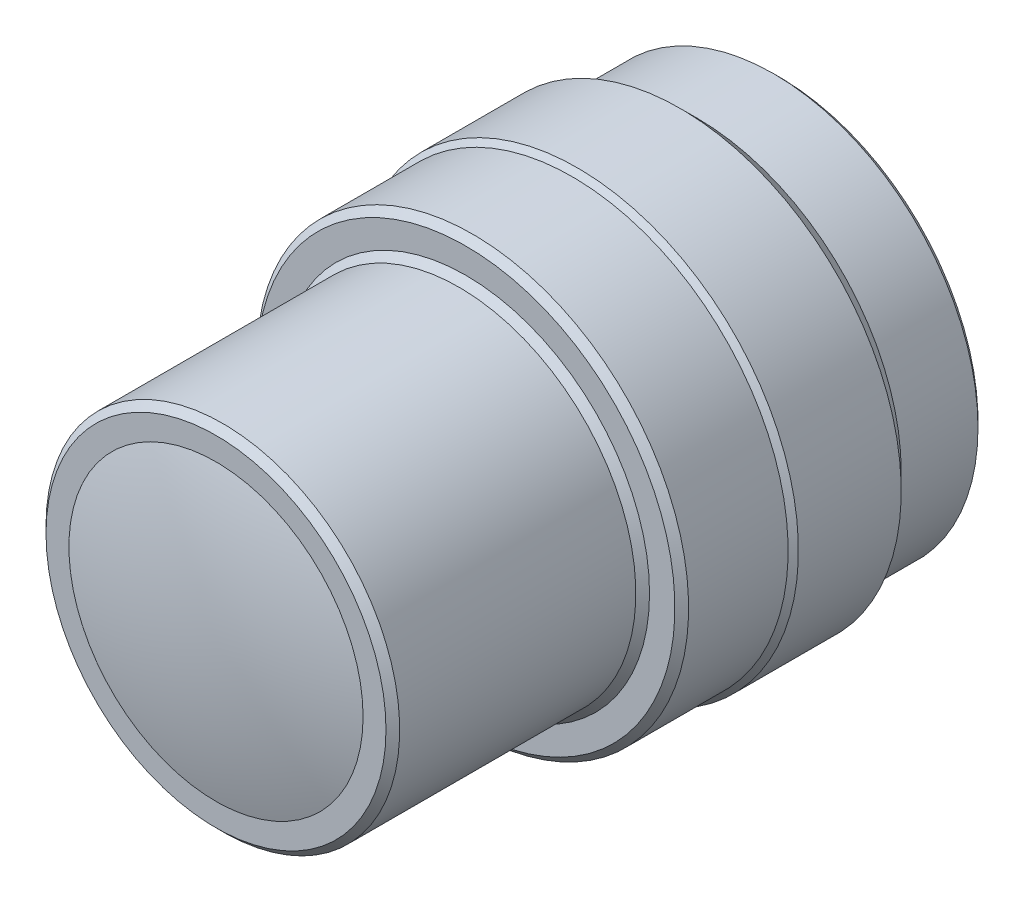
SolidWorks part; units mm, degrees
material "объектив"
ref_plane "Спереди" through (0, 0, 0) normal (0, 0, 1) x (1, 0, 0)
ref_plane "Сверху" through (0, 0, 0) normal (0, 1, 0) x (1, 0, 0)
ref_plane "Справа" through (0, 0, 0) normal (1, 0, 0) x (0, 0, -1)
sketch "Эскиз1" plane through (0, 0, 0) normal (0, 1, 0) x (1, 0, 0)
  line L0 (0, 0) -> (12.7, 0)
  line L1 (12.7, 0) -> (12.7, -3)
  line L2 (12.7, -3) -> (15, -3)
  line L3 (15, -3) -> (15, -4)
  line L4 (15, -4) -> (29, -4)
  line L5 (29, -4) -> (29.8, -4.8)
  line L6 (29.8, -4.8) -> (29.8, -16)
  line L7 (29.8, -16) -> (32.25, -18.45)
  line L8 (32.25, -18.45) -> (32.25, -33.45)
  line L9 (32.25, -33.45) -> (31.5, -34.2)
  line L10 (31.5, -34.2) -> (31.5, -48.72)
  line L11 (31.5, -48.72) -> (30.5, -49.72)
  line L12 (30.5, -49.72) -> (26.8, -49.72)
  line L13 (26.8, -49.72) -> (25.8, -50.72)
  line L14 (25.8, -50.72) -> (25.8, -85.17)
  line L15 (25.8, -85.17) -> (24.8, -86.17)
  line L16 (24.8, -86.17) -> (0, -86.17)
  line L17 (0, -86.17) -> (0, 0) construction
  line L18 (31.5, -4.8) -> (27.8124, -4.8) construction
  line L19 (33.788, -18.45) -> (30.2928, -18.45) construction
  line L20 (31.5, -16) -> (27.8124, -16) construction
  line L21 (33.3304, -33.45) -> (31.0645, -33.45) construction
  line L22 (33.3304, -34.2) -> (29.8, -34.2) construction
  line L23 (0, 0) -> (0, -86.17)
  dimension "D1" = 12.7
  dimension "D2" = 15
  dimension "D3" = 29.8
  dimension "D4" = 32.25
  dimension "D5" = 31.5
  dimension "D6" = 25.8
  dimension "D7" = 135
  dimension "D8" = 135
  dimension "D9" = 135
  dimension "D10" = 135
  dimension "D11" = 135
  dimension "D12" = 135
  dimension "D13" = 15.45
  dimension "D14" = 46.72
  dimension "D15" = 83.17
  dimension "D16" = 3
  dimension "D17" = 1
  dimension "D18" = 29
  dimension "D19" = 1
  dimension "D20" = 1
  dimension "D21" = 1
  dimension "D22" = 15
revolve "Повернуть1" add sketch "Эскиз1" angle 360 about L23
sketch "Эскиз2" plane through (0, 0, 0) normal (0, 1, 0) x (1, 0, 0)
  line L0 (0, -86.17) -> (0, -89.17)
  line L1 (0, -86.17) -> (21.4594, -86.17)
  line L2 (24.8, -86.17) -> (0, -86.17) construction
  line L3 (0, -2.4824) -> (0, 39.1914) construction
  line L4 (0, 0) -> (0, -86.17) construction
  arc A0 (0, -89.17) -> (21.4594, -86.17) centre (0, -10.919) ccw
  dimension "D2" = 3
  dimension "D3" = 21.4594
revolve "Повернуть2" add sketch "Эскиз2" angle 360 about L3
